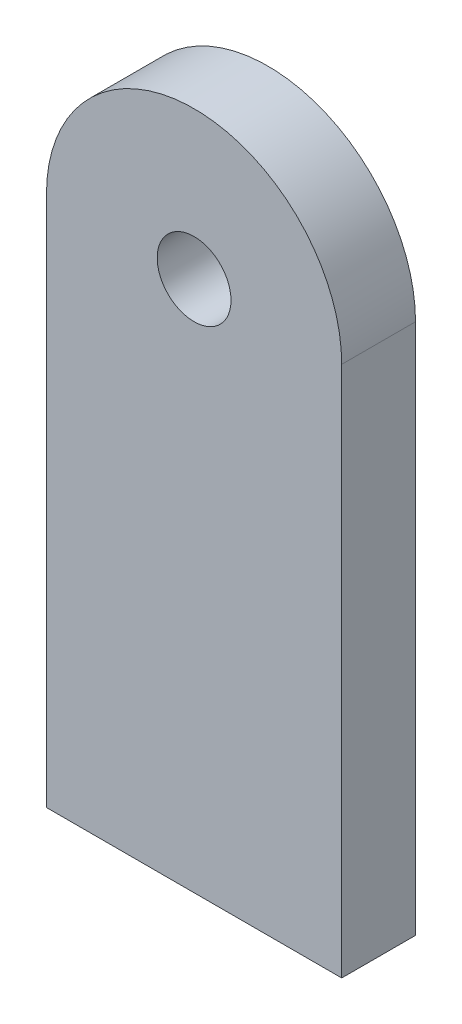
SolidWorks part; units mm, degrees
material "Gray Cast Iron"
ref_plane "Front Plane" through (0, 0, 0) normal (0, 0, 1) x (1, 0, 0)
ref_plane "Top Plane" through (0, 0, 0) normal (0, 1, 0) x (1, 0, 0)
ref_plane "Right Plane" through (0, 0, 0) normal (1, 0, 0) x (0, 0, -1)
sketch "Sketch1" plane through (0, 0, 0) normal (0, 0, 1) x (1, 0, 0)
  line L0 (0, 0) -> (100, 0)
  line L1 (100, 0) -> (100, 180)
  line L3 (0, 180) -> (0, 0)
  arc A0 (0, 180) -> (100, 180) centre (50, 180) cw
  circle A1 centre (50, 180) radius 12.5
  dimension "D3" = 25
  dimension "D1" = 100
  dimension "D2" = 180
extrude "Boss-Extrude1" add sketch "Sketch1" along normal blind 25
